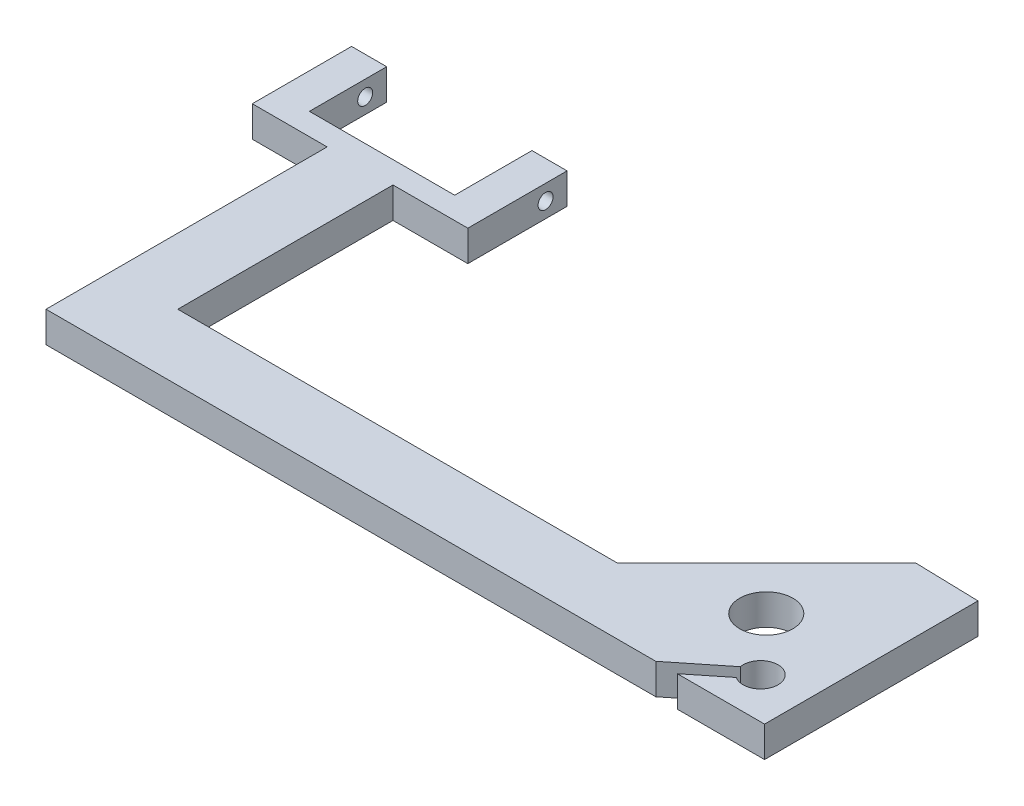
SolidWorks part; units mm, degrees
ref_plane "Front Plane" through (0, 0, 0) normal (0, 0, 1) x (1, 0, 0)
ref_plane "Top Plane" through (0, 0, 0) normal (0, 1, 0) x (1, 0, 0)
ref_plane "Right Plane" through (0, 0, 0) normal (1, 0, 0) x (0, 0, -1)
sketch "Sketch1" plane through (0, 0, 0) normal (0, 1, 0) x (1, 0, 0)
  line L0 (-86.41, -26.1652) -> (-86.41, -43.7652)
  line L1 (-86.41, -43.7652) -> (-53.34, -43.7652)
  line L2 (-53.34, -43.7652) -> (-53.34, -26.1652)
  line L3 (-53.34, -26.1652) -> (-45.34, -26.1652)
  line L4 (-45.34, -26.1652) -> (-45.34, -48.7652)
  line L5 (-45.34, -48.7652) -> (-62.375, -48.7652)
  line L6 (-86.41, -26.1652) -> (-94.41, -26.1652)
  line L7 (-94.41, -26.1652) -> (-94.41, -48.7652)
  line L8 (-94.41, -48.7652) -> (-77.375, -48.7652)
  line L9 (-77.375, -48.7652) -> (-77.375, -112.7652)
  line L10 (-62.375, -48.7652) -> (-62.375, -97.7652)
  line L11 (-77.375, -112.7652) -> (37.625, -112.7652)
  line L12 (-62.375, -97.7652) -> (37.625, -97.7652)
  line L32 (71.6, -63.7902) -> (37.625, -97.7652)
  line L34 (86.215, -112.7652) -> (86.215, -64.1752)
  line L35 (72.1405, -104.204) -> (61.4476, -112.7652)
  line L36 (66.35, -112.7652) -> (73.8211, -106.7835)
  line L37 (66.35, -112.7652) -> (86.215, -112.7652)
  line L38 (61.4476, -112.7652) -> (37.625, -112.7652)
  line L39 (71.6, -63.7902) -> (86.215, -64.1752)
  circle A2 centre (64.6, -90.7652) radius 6.05
  arc A3 (73.8211, -106.7835) -> (72.1405, -104.204) centre (76.045, -103.4975) ccw
  dimension "D12" = 7
  dimension "D13" = 12.1
  dimension "D1" = 8
  dimension "D2" = 17.6
  dimension "D3" = 5
  dimension "D4" = 33.07
  dimension "D5" = 100
  dimension "D6" = 15
  dimension "D7" = 49
  dimension "D8" = 15
  dimension "D14" = 4.9023
extrude "Boss-Extrude1" add sketch "Sketch1" along normal blind 7
sketch "Sketch3" plane through (-45.34, 0, 0) normal (1, 0, 0) x (0, 0, -1)
  line L0 (-26.1652, 7) -> (-26.1652, 0) construction
  line L1 (-48.7652, 7) -> (-26.1652, 7) construction
  line L2 (-48.7652, 0) -> (-26.1652, 0) construction
  circle A0 centre (-31.0652, 3.5) radius 1.7
  dimension "D1" = 3.4
  dimension "D3" = 3.5
  dimension "D4" = 3.5
  dimension "D2" = 4.9
extrude "Cut-Extrude2" cut sketch "Sketch3" against normal blind 60
